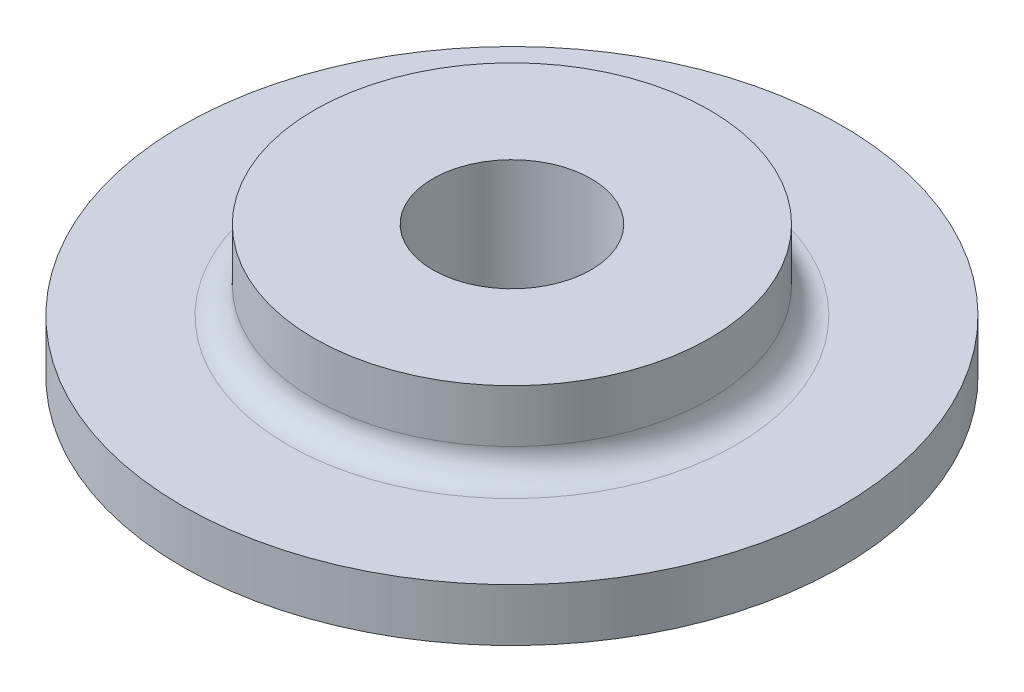
SolidWorks part; units mm, degrees
ref_plane "前视基准面" through (0, 0, 0) normal (0, 0, 1) x (1, 0, 0)
ref_plane "上视基准面" through (0, 0, 0) normal (0, 1, 0) x (1, 0, 0)
ref_plane "右视基准面" through (0, 0, 0) normal (1, 0, 0) x (0, 0, -1)
sketch "草图1" plane through (0, 0, 0) normal (0, 1, 0) x (1, 0, 0)
  circle A0 centre (0, 0) radius 12.5
  dimension "D1" = 25
extrude "凸台-拉伸1" add sketch "草图1" along normal blind 2
sketch "草图2" plane through (0, 2, 0) normal (0, 1, 0) x (1, 0, 0)
  circle A0 centre (0, 0) radius 7.5
  dimension "D1" = 15
extrude "凸台-拉伸2" add sketch "草图2" along normal blind 3
fillet "圆角1" radius 1 1 edges at (0, 2, 7.5)
sketch "草图3" plane through (0, 5, 0) normal (0, 1, 0) x (1, 0, 0)
  circle A0 centre (0, 0) radius 3
  dimension "D1" = 6
extrude "切除-拉伸1" cut sketch "草图3" against normal up to next
